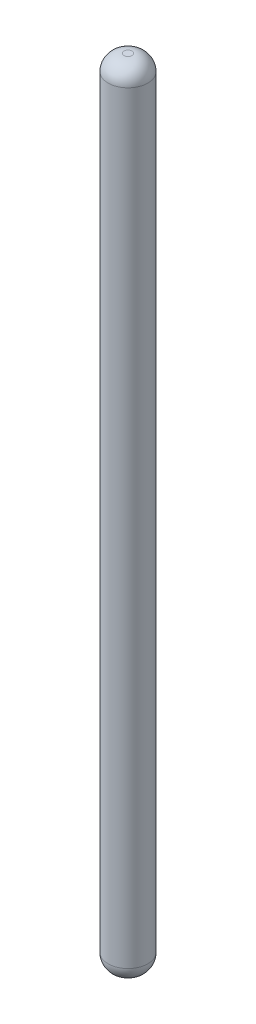
SolidWorks part; units mm, degrees
ref_plane "Front Plane" through (0, 0, 0) normal (0, 0, 1) x (1, 0, 0)
ref_plane "Top Plane" through (0, 0, 0) normal (0, 1, 0) x (1, 0, 0)
ref_plane "Right Plane" through (0, 0, 0) normal (1, 0, 0) x (0, 0, -1)
sketch "Sketch1" plane through (0, 0, 0) normal (0, 1, 0) x (1, 0, 0)
  circle A0 centre (0, 0) radius 50
  dimension "D1" = 100
extrude "Boss-Extrude1" add sketch "Sketch1" along normal mid plane 2000
fillet "Fillet1" radius 40 2 edges at (0, 1000, 50) (0, -1000, 50)
